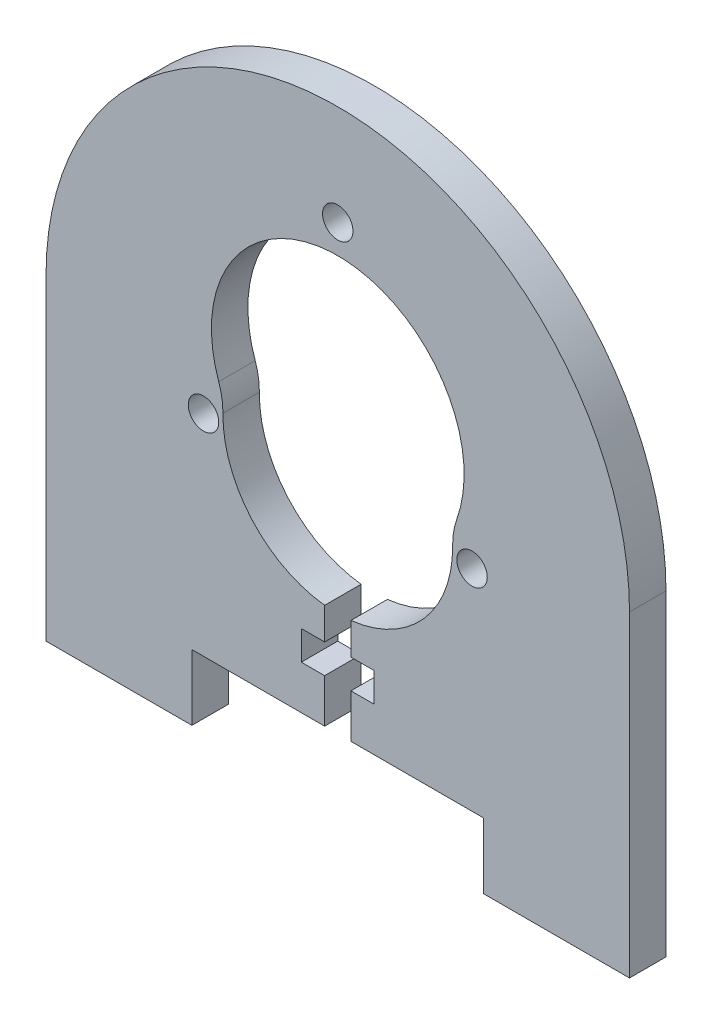
SolidWorks part; units mm, degrees
ref_plane "Front Plane" through (0, 0, 0) normal (0, 0, 1) x (1, 0, 0)
ref_plane "Top Plane" through (0, 0, 0) normal (0, 1, 0) x (1, 0, 0)
ref_plane "Right Plane" through (0, 0, 0) normal (1, 0, 0) x (0, 0, -1)
sketch "Sketch1" plane through (0, 0, 0) normal (0, 0, 1) x (1, 0, 0)
  line L0 (-25.4, 16.9649) -> (25.4, 16.9649) construction
  line L1 (25.4, -13.8001) -> (-25.4, -13.8001)
  line L2 (25.4, -13.8001) -> (25.4, 13.8001)
  line L3 (25.4, 13.8001) -> (-25.4, 13.8001) construction
  line L4 (-25.4, -13.8001) -> (-25.4, 13.8001)
  line L5 (25.4, -13.8001) -> (-25.4, 13.8001) construction
  line L6 (25.4, 13.8001) -> (-25.4, -13.8001) construction
  line L7 (0, 39.2001) -> (0, -13.8001) construction
  arc A0 (-25.4, 13.8001) -> (25.4, 13.8001) centre (0, 13.8001) cw
  circle A3 centre (0, 16.9649) radius 16.5 construction
  circle A4 centre (0, 22.9649) radius 2.5 construction
  point P0 (0, 0)
  dimension "D2" = 33
  dimension "D4" = 5
  dimension "D1" = 30.765
  dimension "D3" = 6
  dimension "D5" = 50.8
  dimension "D6" = 22.2352
extrude "Boss-Extrude1" add sketch "Sketch1" along normal blind 3.175
sketch "Sketch2" plane through (0, 0, 3.175) normal (0, 0, 1) x (1, 0, 0)
  circle A0 centre (0, 16.9649) radius 11
  dimension "D1" = 22
extrude "Cut-Extrude1" cut sketch "Sketch2" against normal up to next
sketch "Sketch3" plane through (0, 0, 3.175) normal (0, 0, 1) x (1, 0, 0)
  line L0 (25.4, -13.8001) -> (-25.4, -13.8001) construction
  line L1 (-12.7, -13.8001) -> (12.7, -13.8001)
  line L2 (-12.7, -13.8001) -> (-12.7, -8.0851)
  line L3 (-12.7, -8.0851) -> (12.7, -8.0851)
  line L4 (12.7, -13.8001) -> (12.7, -8.0851)
  line L6 (0, 39.2001) -> (0, -13.8001) construction
  point P6 (0, -8.0851)
  dimension "D1" = 5.715
  dimension "D2" = 25.4
extrude "Cut-Extrude2" cut sketch "Sketch3" against normal up to next
sketch "Sketch4" plane through (0, 0, 3.175) normal (0, 0, 1) x (1, 0, 0)
  line L0 (-25.4, -13.8001) -> (-12.7, -13.8001) construction
  line L1 (25.4, -13.8001) -> (-25.4, -13.8001) construction
  line L2 (-12.7, -8.0851) -> (-12.7, -13.8001) construction
  line L3 (-20.2866, -1014.3325) -> (-20.2866, 48985.6675) construction
  line L4 (0, -1.7463) -> (0, 1.7463) construction
  line L5 (-18.6991, 1.4399) -> (-21.8741, 1.4399)
  line L6 (-18.6991, 1.4399) -> (-18.6991, 7.7899)
  line L7 (-18.6991, 7.7899) -> (-21.8741, 7.7899)
  line L8 (-21.8741, 1.4399) -> (-21.8741, 7.7899)
  line L9 (-18.6991, 1.4399) -> (-21.8741, 7.7899) construction
  line L10 (-18.6991, 7.7899) -> (-21.8741, 1.4399) construction
  line L11 (18.6991, -1.1001) -> (21.8741, -7.4501) construction
  line L12 (-18.6991, -7.4501) -> (-21.8741, -7.4501)
  line L13 (-18.6991, -7.4501) -> (-18.6991, -1.1001)
  line L14 (-18.6991, -1.1001) -> (-21.8741, -1.1001)
  line L15 (-21.8741, -7.4501) -> (-21.8741, -1.1001)
  line L16 (-18.6991, -7.4501) -> (-21.8741, -1.1001) construction
  line L17 (-18.6991, -1.1001) -> (-21.8741, -7.4501) construction
  line L18 (18.6991, -7.4501) -> (21.8741, -1.1001) construction
  line L19 (18.6991, 7.7899) -> (21.8741, 1.4399) construction
  line L20 (18.6991, 1.4399) -> (21.8741, 7.7899) construction
  line L21 (21.8741, -7.4501) -> (21.8741, -1.1001)
  line L22 (18.6991, -1.1001) -> (21.8741, -1.1001)
  line L23 (18.6991, -7.4501) -> (18.6991, -1.1001)
  line L24 (18.6991, -7.4501) -> (21.8741, -7.4501)
  line L25 (21.8741, 1.4399) -> (21.8741, 7.7899)
  line L26 (18.6991, 7.7899) -> (21.8741, 7.7899)
  line L27 (18.6991, 1.4399) -> (18.6991, 7.7899)
  line L28 (18.6991, 1.4399) -> (21.8741, 1.4399)
  point P7 (-20.2866, -13.8001)
  point P9 (-20.2866, 4.6149)
  point P17 (-20.2866, -4.2751)
  point P23 (-19.05, -13.8001)
  point P35 (20.2866, -4.2751)
  point P36 (20.2866, 4.6149)
  dimension "D1" = 6.35
  dimension "D2" = 6.35
  dimension "D3" = 3.175
  dimension "D4" = 3.175
  dimension "D5" = 6.35
  dimension "D6" = 2.54
  dimension "D7" = 1.2366
extrude "Cut-Extrude3" [suppressed] cut sketch "Sketch4" against normal up to next
sketch "Sketch5" plane through (0, 0, 3.175) normal (0, 0, 1) x (1, 0, 0)
  line L0 (0, 39.2001) -> (0, -13.8001) construction
  line L1 (3.175, -4.2751) -> (1.143, -4.2751)
  line L2 (3.175, -4.2751) -> (3.175, -1.7351)
  line L3 (3.175, -1.7351) -> (1.143, -1.7351)
  line L4 (-3.175, -4.2751) -> (-3.175, -1.7351)
  line L5 (3.175, -4.2751) -> (-3.175, -1.7351) construction
  line L6 (3.175, -1.7351) -> (-3.175, -4.2751) construction
  line L7 (12.7, -8.0851) -> (-12.7, -8.0851) construction
  line L8 (-1.143, -1.7351) -> (-3.175, -1.7351)
  line L9 (-1.143, -8.0851) -> (1.143, -8.0851)
  line L10 (-1.143, -8.0851) -> (-1.143, -4.2751)
  line L11 (-1.143, 7.1549) -> (1.143, 7.1549)
  line L12 (1.143, -8.0851) -> (1.143, -4.2751)
  line L13 (-1.143, -1.7351) -> (-1.143, 7.1549)
  line L14 (1.143, -1.7351) -> (1.143, 7.1549)
  line L15 (-1.143, -4.2751) -> (-3.175, -4.2751)
  point P0 (0, -3.0051)
  point P14 (0, 7.1549)
  dimension "D1" = 6.35
  dimension "D2" = 2.54
  dimension "D3" = 3.81
  dimension "D4" = 2.286
  dimension "D5" = 15.24
extrude "Cut-Extrude4" cut sketch "Sketch5" against normal up to next
sketch "Sketch6" plane through (0, 0, 0) normal (0, 0, 1) x (1, 0, 0)
  line L0 (0, 39.2001) -> (0, -13.8001) construction
  circle A0 centre (0, 30.4649) radius 1.325
  circle A1 centre (11.6913, 10.2149) radius 1.325
  circle A2 centre (-11.6913, 10.2149) radius 1.325
  point P10 (0, 16.9649)
  dimension "D1" = 2.65
  dimension "D3" = 13.5
  dimension "D2" = 3
extrude "Cut-Extrude6" cut sketch "Sketch6" along normal through all
sketch "Sketch7" plane through (0, 0, 0) normal (0, 0, 1) x (1, 0, 0)
  line L0 (0, 39.2001) -> (0, -13.8001) construction
  circle A0 centre (0, 10.9649) radius 10
  dimension "D1" = 20
  dimension "D2" = 6
extrude "Cut-Extrude7" cut sketch "Sketch7" along normal through all
fillet "Fillet1" radius 6.35 2 edges at (9.9216, 12.2149, 1.5875) (-9.9216, 12.2149, 1.5875)
equation "\"D2@Sketch1\"=33mm"
equation "\"D1@Sketch1\"=0.75+\"thickness0.25\"+\"motor offset\""
equation "\"t\"=0.125"
equation "\"D1@Boss-Extrude1\"=\"t\""
equation "\"D4@Sketch4\"=\"t\""
equation "\"D3@Sketch4\"=\"t\""
equation "\"motor offset\"=6mm"
equation "\"thickness0.25\"=0.225in"
equation "\"thickness0.125\"=0.122in"
equation "\"motor diameter\"= 33mm"
equation "\"D3@Sketch1\"=\"motor offset\""
equation "\"D1@Sketch3\"=\"thickness0.25\""
equation "\"D2@Sketch7\"=\"motor offset\""
